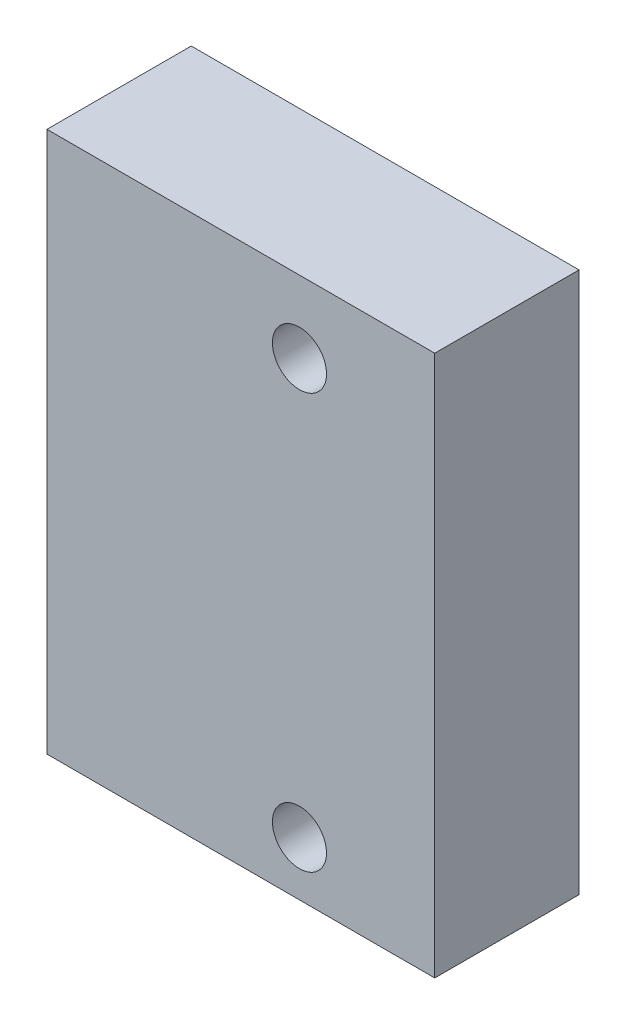
SolidWorks part; units mm, degrees
ref_plane "前视基准面" through (0, 0, 0) normal (0, 0, 1) x (1, 0, 0)
ref_plane "上视基准面" through (0, 0, 0) normal (0, 1, 0) x (1, 0, 0)
ref_plane "右视基准面" through (0, 0, 0) normal (1, 0, 0) x (0, 0, -1)
other "Configuration Table"
sketch "草图1" plane through (0, 0, 0) normal (0, 0, 1) x (1, 0, 0)
  line L0 (0, 0) -> (-43, 0)
  line L1 (-43, 0) -> (-43, 60)
  line L11 (-43, 60) -> (0, 60)
  line L12 (0, 60) -> (0, 0)
  dimension "D1" = 43
  dimension "D2" = 60
extrude "凸台-拉伸3" add sketch "草图1" along normal blind 16
sketch "草图2" plane through (0, 0, 0) normal (0, 0, -1) x (-1, 0, 0)
  line L1 (43, 0) -> (0, 0) construction
  circle A0 centre (15, 52) radius 3
  circle A1 centre (15, 6) radius 3
  point P6 (15, 54)
  point P7 (15, 52)
  dimension "D1" = 6
  dimension "D2" = 6
  dimension "D3" = 46
  dimension "D4" = 6
extrude "切除-拉伸1" cut sketch "草图2" against normal through all
sketch "草图3" plane through (-43, 0, 0) normal (-1, 0, 0) x (0, 0, 1)
  line L0 (16, 60) -> (0, 60) construction
  line L1 (16, 0) -> (0, 0) construction
  line L2 (0, 60) -> (0, 0) construction
  circle A0 centre (8, 42) radius 3
  circle A1 centre (8, 18) radius 3
  dimension "D1" = 6
  dimension "D2" = 6
  dimension "D3" = 18
  dimension "D4" = 18
  dimension "D5" = 8
  dimension "D6" = 8
hole_wizard "M6 螺纹孔1" positions "草图4" profile "草图5" tap size "M6" standard "GB"
sketch "草图4" plane through (-43, 0, 0) normal (-1, 0, 0) x (0, 0, 1)
  point P0 (8, 42)
  point P3 (8, 18)
sketch "草图5" plane through (-43, 42, 8) normal (0, 1, 0) x (0, 0, 1)
  line L0 (0, 0) -> (0, 11.5022)
  line L1 (0, 11.5022) -> (2.5, 10)
  line L2 (2.5, 10) -> (2.5, 0)
  line L5 (2.5, 0) -> (0, 0)
  line L10 (0, 11.5022) -> (-2.5, 10) construction
  line L11 (0, -6.35) -> (0, 107.95) construction
  dimension "螺纹孔钻头直径" = 5
  dimension "螺纹孔钻头深度" = 10
  dimension "导头角度" = 118
cosmetic thread "孔螺蚊线1" parameters "D1"=8, "D2"=6
cosmetic thread "孔螺蚊线2" parameters "D1"=8, "D2"=6
